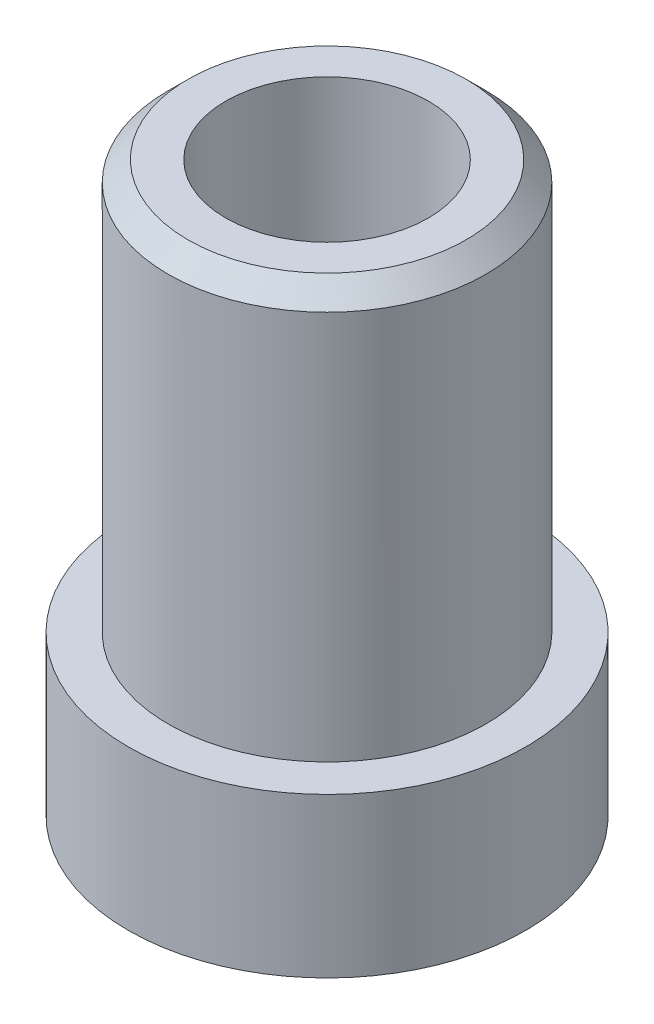
SolidWorks part; units mm, degrees
ref_plane "前视基准面" through (0, 0, 0) normal (0, 0, 1) x (1, 0, 0)
ref_plane "上视基准面" through (0, 0, 0) normal (0, 1, 0) x (1, 0, 0)
ref_plane "右视基准面" through (0, 0, 0) normal (1, 0, 0) x (0, 0, -1)
sketch "草图1" plane through (0, 0, 0) normal (0, 1, 0) x (1, 0, 0)
  circle A0 centre (0, 0) radius 4
  dimension "D1" = 8
extrude "凸台-拉伸1" add sketch "草图1" along normal mid plane 14.3
sketch "草图2" plane through (0, 0, 0) normal (0, 0, 1) x (1, 0, 0)
  line L0 (4, -7.15) -> (5, -7.15)
  line L1 (5, -7.15) -> (5, -3.15)
  line L2 (5, -3.15) -> (4, -3.15)
  line L3 (4, -3.15) -> (4, -7.15)
  dimension "D1" = 1
  dimension "D2" = 4
revolve "旋转1" add sketch "草图2" angle 360 about axis through (0, 7.15, 0) along (0, -1, 0)
chamfer "倒角1" distance 0.5 angle 45 1 edges at (0, 7.15, 4)
hole_wizard "Ø5.1 (5.1) 直径孔1" positions "草图5" profile "草图4" hole size "Ø5.1" standard "GB" end condition through all
sketch "草图5" plane through (0, -7.15, 0) normal (0, -1, 0) x (-1, 0, 0)
  point P0 (0, 0)
sketch "草图4" plane through (0, -7.15, 0) normal (1, 0, 0) x (0, 0, -1)
  line L0 (0, 0) -> (0, 14.3)
  line L1 (0, 14.3) -> (2.55, 14.3)
  line L2 (2.55, 14.3) -> (2.55, 0)
  line L5 (2.55, 0) -> (0, 0)
  line L11 (0, -6.35) -> (0, 107.95) construction
  dimension "通孔孔直径" = 5.1
  dimension "通孔孔深度" = 14.3
